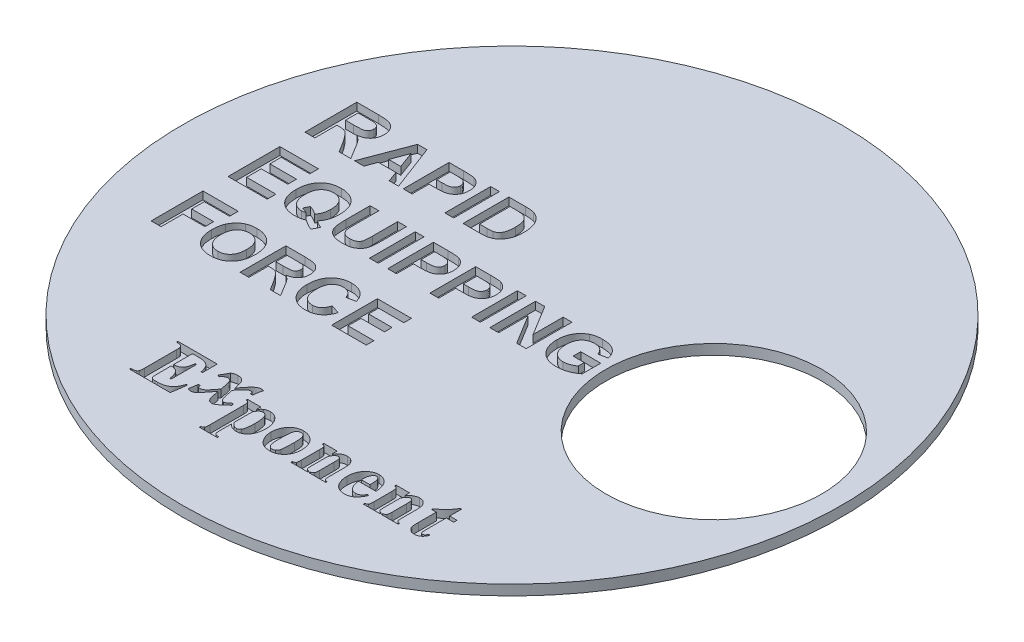
SolidWorks part; units mm, degrees
material "6061 Alloy"
ref_plane "Front Plane" through (0, 0, 0) normal (0, 0, 1) x (1, 0, 0)
ref_plane "Top Plane" through (0, 0, 0) normal (0, 1, 0) x (1, 0, 0)
ref_plane "Right Plane" through (0, 0, 0) normal (1, 0, 0) x (0, 0, -1)
sketch "Sketch1" plane through (0, 0, 0) normal (0, 1, 0) x (1, 0, 0)
  circle A0 centre (0, 0) radius 20.828
  dimension "D1" = 41.656
extrude "Boss-Extrude1" add sketch "Sketch1" along normal blind 1.27
sketch "Sketch2" plane through (0, 1.27, 0) normal (0, 1, 0) x (1, 0, 0)
  circle A0 centre (0, 0) radius 20.32
  circle A1 centre (0, 0) radius 20.828
  circle A2 centre (0, 0) radius 20.828 construction
  dimension "D1" = 0.508
extrude "Cut-Extrude2" cut sketch "Sketch2" against normal blind 0.635
sketch "Sketch3" plane through (0, 1.27, 0) normal (0, 1, 0) x (1, 0, 0)
  line L0 (20.828, 3.7545) -> (20.828, -12.2477) construction
  line L1 (0, 0) -> (20.828, 0) construction
  line L2 (18.6677, 2.8354) -> (18.6677, -2.8354)
  line L3 (9.3332, 2.8354) -> (9.3332, -2.8354)
  arc A0 (9.3332, -2.8354) -> (18.6677, -2.8354) centre (14.0005, 0) ccw
  arc A2 (18.6677, 2.8354) -> (9.3332, 2.8354) centre (14.0005, 0) ccw
  circle A3 centre (0, 0) radius 20.828 construction
  dimension "D1" = 10.922
  dimension "D3" = 4.6672
  dimension "D2" = 14.0005
extrude "Cut-Extrude3" cut sketch "Sketch3" against normal through all
chamfer "Chamfer1" [suppressed] distance 0.127 angle 45
sketch "Sketch12" plane through (0, 0, 0) normal (0, -1, 0) x (1, 0, 0)
  line L1 (-7.6581, 18.2626) -> (5.6769, 18.2626)
  line L2 (-9.2456, 16.6751) -> (-9.2456, 3.3401)
  line L3 (-7.6581, 1.7526) -> (5.6769, 1.7526)
  line L4 (7.2644, 16.6751) -> (7.2644, 3.3401)
  line L5 (-9.2456, 18.2626) -> (7.2644, 1.7526) construction
  line L6 (-9.2456, 1.7526) -> (7.2644, 18.2626) construction
  arc A0 (-9.2456, 16.6751) -> (-7.6581, 18.2626) centre (-7.6581, 16.6751) cw
  arc A1 (-7.6581, 1.7526) -> (-9.2456, 3.3401) centre (-7.6581, 3.3401) cw
  arc A2 (7.2644, 3.3401) -> (5.6769, 1.7526) centre (5.6769, 3.3401) cw
  arc A3 (7.2644, 16.6751) -> (5.6769, 18.2626) centre (5.6769, 16.6751) ccw
  point P0 (-0.9906, 10.0076)
  dimension "D3" = 16.51
  dimension "D4" = 1.5875
  dimension "D1" = 10.0076
  dimension "D2" = 0.9906
extrude "Cut-Extrude4" [suppressed] cut sketch "Sketch12" against normal blind 0.508
sketch "Sketch13" plane through (0, 0, 0) normal (0, -1, 0) x (1, 0, 0)
  line L0 (-13.1479, -13.7739) -> (-10.5519, -15.8507)
  line L1 (-16.7984, -13.2341) -> (-6.871, -21.176) construction
  line L2 (-13.0111, -16.2639) -> (0, 0) construction
  arc A0 (-10.5519, -15.8507) -> (-13.1479, -13.7739) centre (-10.16, -12.7) ccw
  circle A1 centre (0, 0) radius 20.828 construction
  circle A2 centre (0, 0) radius 20.828 construction
  dimension "D3" = 6.35
  dimension "D4" = 2.7051
  dimension "D1" = 12.7
  dimension "D2" = 10.16
extrude "Cut-Extrude5" [suppressed] cut sketch "Sketch13" against normal through all
sketch "Sketch16" plane through (0, 1.27, 0) normal (0, 1, 0) x (1, 0, 0)
  circle A0 centre (0, 0) radius 20.32
  circle A1 centre (0, 0) radius 22.86
  circle A2 centre (0, 0) radius 20.32 construction
  dimension "D1" = 45.72
extrude "Boss-Extrude2" add sketch "Sketch16" against normal up to surface (1.27 mm away) up to face at (14.0005, 0, 0)
sketch "Sketch17" plane through (0, 1.27, 0) normal (0, 1, 0) x (1, 0, 0)
  circle A0 centre (14.0005, 0) radius 7.493
  arc A3 (18.6677, 2.8354) -> (9.3332, 2.8354) centre (14.0005, 0) ccw construction
  dimension "D1" = 14.986
extrude "Cut-Extrude6" cut sketch "Sketch17" against normal through all
sketch "Sketch18" plane through (0, 0, 0) normal (0, -1, 0) x (1, 0, 0)
  circle A0 centre (0, 0) radius 22.86
  circle A1 centre (0, 0) radius 22.86 construction
extrude "Cut-Extrude7" cut sketch "Sketch18" against normal offset from surface (0.5588 mm away) 0.7112 up to face at (14.0005, 1.27, 7.493)
sketch "Sketch20" plane through (0, 1.27, 0) normal (0, 1, 0) x (1, 0, 0)
  line L0 (-18.542, 3.81) -> (-18.542, -1.524) construction
  line L1 (-18.542, -1.524) -> (-18.542, -6.858) construction
  text T0 "R" font "Arial" height in points 14
  text T1 "E" font "Arial" height in points 14
  text T2 "F" font "Arial" height in points 14
  text T3 "APID" font "Arial" height 3.175
  text T4 "QUIPPING" font "Arial" height 3.175
  text T5 "ORCE" font "Arial" height 3.175
  text T6 "E  ponent" font "Times New Roman" height in points 14
  text T7 "x" font "Palatino Linotype" height in points 14
  dimension "D1" = 3.81
  dimension "D2" = 5.334
  dimension "D3" = 18.542
  dimension "D4" = 3.81
  dimension "D5" = 3.302
  dimension "D6" = 2.794
  dimension "D7" = 16.51
  dimension "D8" = 10.16
  dimension "D9" = 3.429
  dimension "D10" = 0.889
extrude "Cut-Extrude8" cut sketch "Sketch20" against normal offset from surface (0.5334 mm away) 0.1778 up to face at (0, 0.5588, 22.86)
